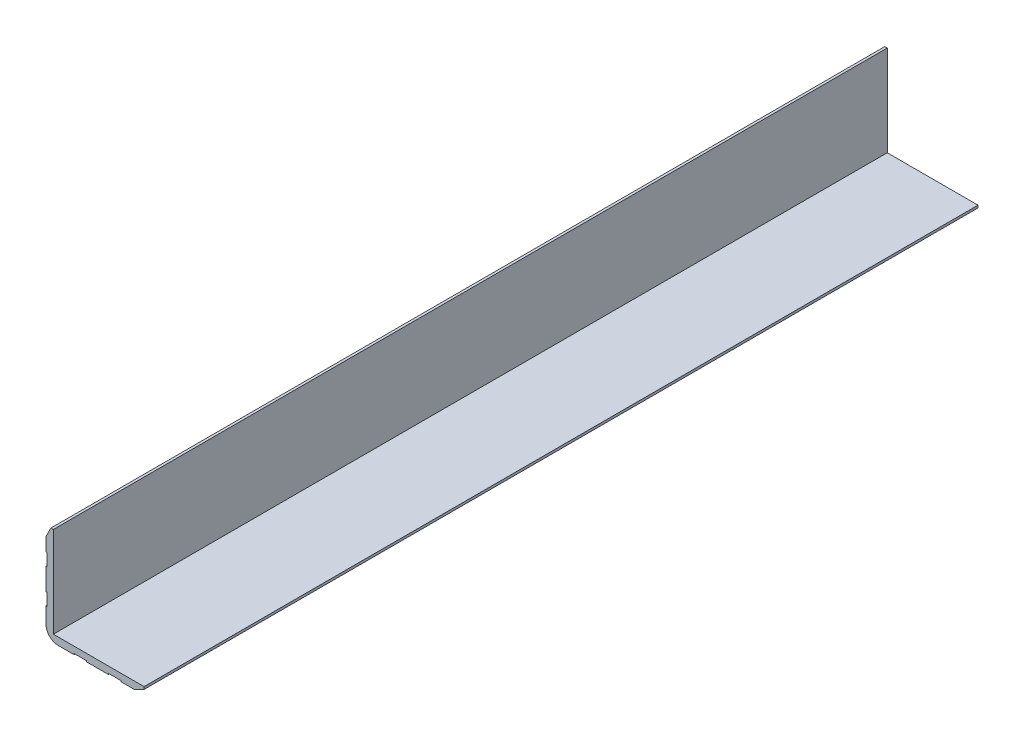
SolidWorks part; units mm, degrees
ref_plane "Front Plane" through (0, 0, 0) normal (0, 0, 1) x (1, 0, 0)
ref_plane "Top Plane" through (0, 0, 0) normal (0, 1, 0) x (1, 0, 0)
ref_plane "Right Plane" through (0, 0, 0) normal (1, 0, 0) x (0, 0, -1)
sketch "Sketch1" plane through (0, 0, 0) normal (0, 0, 1) x (1, 0, 0)
  line L0 (0, 0) -> (0, 18.5)
  line L1 (0, 18.5) -> (-0.5, 18.5)
  line L2 (-0.5, 18.5) -> (-1.5, 16.5)
  line L3 (-1.5, 16.5) -> (-1.5, 13.75)
  line L4 (-1.5, 13.75) -> (-1.3, 13.75)
  line L5 (-1.3, 13.75) -> (-1.3, 11.25)
  line L6 (-1.3, 11.25) -> (-1.5, 11.25)
  line L7 (-1.5, 11.25) -> (-1.5, 6.75)
  line L8 (-1.5, 6.75) -> (-1.3, 6.75)
  line L9 (-1.3, 6.75) -> (-1.3, 4.25)
  line L10 (-1.3, 4.25) -> (-1.5, 4.25)
  line L11 (-1.5, 4.25) -> (-1.5, 1)
  line L12 (1, -1.5) -> (4.25, -1.5)
  line L13 (4.25, -1.5) -> (4.25, -1.3)
  line L14 (4.25, -1.3) -> (6.75, -1.3)
  line L15 (6.75, -1.3) -> (6.75, -1.5)
  line L16 (6.75, -1.5) -> (11.25, -1.5)
  line L17 (11.25, -1.5) -> (11.25, -1.3)
  line L18 (11.25, -1.3) -> (13.75, -1.3)
  line L19 (13.75, -1.3) -> (13.75, -1.5)
  line L20 (13.75, -1.5) -> (16.5, -1.5)
  line L21 (16.5, -1.5) -> (18.5, -0.5)
  line L22 (18.5, -0.5) -> (18.5, 0)
  line L23 (18.5, 0) -> (0, 0)
  arc A0 (1, -1.5) -> (-1.5, 1) centre (1, 1) cw
  dimension "D9" = 2.5
  dimension "D1" = 18.5
  dimension "D2" = 5.75
  dimension "D3" = 0.5
  dimension "D4" = 1.5
  dimension "D5" = 0.2
  dimension "D6" = 2.5
  dimension "D7" = 2
  dimension "D8" = 4.5
  dimension "D10" = 1.5
  dimension "D11" = 0.5
  dimension "D12" = 2
extrude "Length" add sketch "Sketch1" along normal blind 170
